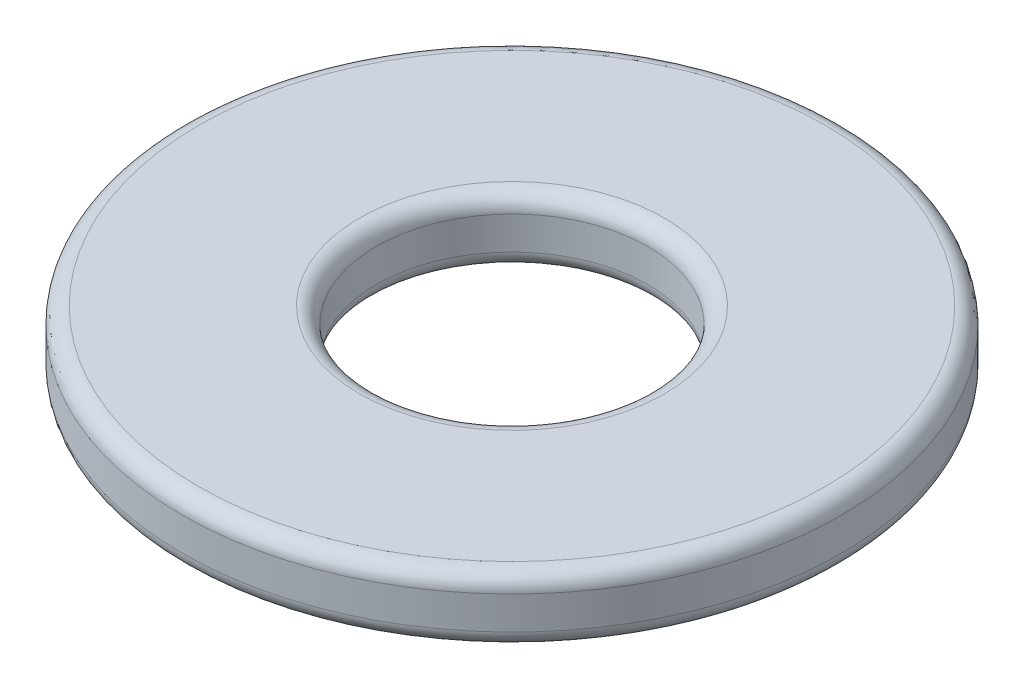
SolidWorks part; units mm, degrees
ref_plane "Front Plane" through (0, 0, 0) normal (0, 0, 1) x (1, 0, 0)
ref_plane "Top Plane" through (0, 0, 0) normal (0, 1, 0) x (1, 0, 0)
ref_plane "Right Plane" through (0, 0, 0) normal (1, 0, 0) x (0, 0, -1)
sketch "Main Sketch" plane through (0, 0, 0) normal (0, 1, 0) x (1, 0, 0)
  circle A0 centre (0, 0) radius 1.65
  circle A1 centre (0, 0) radius 4
  dimension "D1" = 3.3
  dimension "D2" = 8
extrude "Washer Main" add sketch "Main Sketch" along normal blind 0.8
fillet "Edge Fillets" radius 0.2 4 edges at (0, 0, 4) (0, 0.8, 4) (0, 0, 1.65) (0, 0.8, 1.65)
